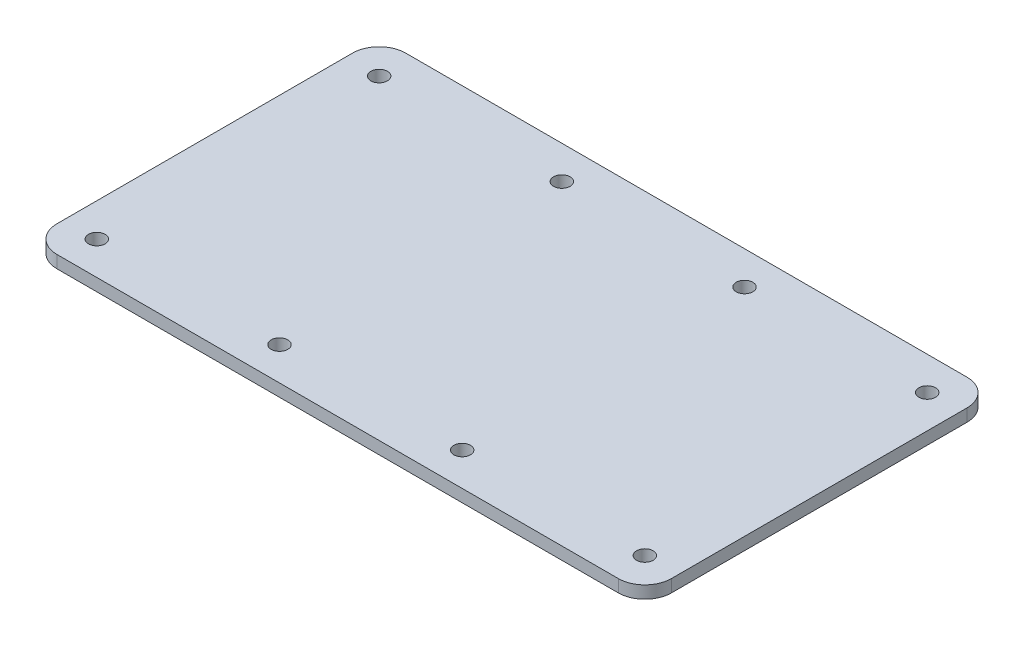
SolidWorks part; units mm, degrees
material "Silicon Rubber"
ref_plane "Front Plane" through (0, 0, 0) normal (0, 0, 1) x (1, 0, 0)
ref_plane "Top Plane" through (0, 0, 0) normal (0, 1, 0) x (1, 0, 0)
ref_plane "Right Plane" through (0, 0, 0) normal (1, 0, 0) x (0, 0, -1)
other "Configuration Table"
sketch "Sketch1" plane through (0, 0, 0) normal (0, 1, 0) x (1, 0, 0)
  line L1 (0, 0) -> (234.95, 0)
  line L2 (0, 0) -> (0, 133.35)
  line L3 (0, 133.35) -> (234.95, 133.35)
  line L4 (234.95, 0) -> (234.95, 133.35)
  dimension "D1" = 133.35
  dimension "D2" = 234.95
extrude "Boss-Extrude1" add sketch "Sketch1" along normal blind 4.7625
fillet "Fillet1" radius 10.16 4 edges at (0, 2.3813, -133.35) (0, 2.3813, 0) (234.95, 2.3813, -133.35) (234.95, 2.3813, 0)
hole_wizard "1/4 (0.25) Diameter Hole3" positions "Sketch6" profile "Sketch7" hole size "1/4" standard "ANSI Inch" end condition through all
sketch "Sketch6" plane through (0, 4.7625, 0) normal (0, 1, 0) x (1, 0, 0)
  line L0 (0, 123.19) -> (0, 10.16) construction
  line L1 (224.79, 133.35) -> (10.16, 133.35) construction
  line L4 (234.95, 10.16) -> (234.95, 123.19) construction
  point P0 (12.7, 120.65)
  point P2 (82.55, 120.65)
  point P4 (152.4, 120.65)
  point P6 (222.25, 120.65)
  dimension "D1" = 12.7
  dimension "D2" = 12.7
  dimension "D3" = 69.85
  dimension "D4" = 69.85
  dimension "D5" = 12.7
sketch "Sketch7" plane through (12.7, 4.7625, -120.65) normal (1, 0, 0) x (0, 0, 1)
  line L0 (0, 0) -> (0, 4.7625)
  line L1 (0, 4.7625) -> (3.175, 4.7625)
  line L2 (3.175, 4.7625) -> (3.175, 0)
  line L5 (3.175, 0) -> (0, 0)
  line L11 (0, -6.35) -> (0, 107.95) construction
  dimension "Thru Hole Dia." = 6.35
  dimension "Thru Hole Depth" = 4.7625
ref_plane "Plane1" through (0, 0, -66.675) normal (0, 0, 1) x (1, 0, 0)
mirror "Mirror1" about plane through (0, 0, -66.675) normal (0, 0, 1) of "1/4 (0.25) Diameter Hole3"
